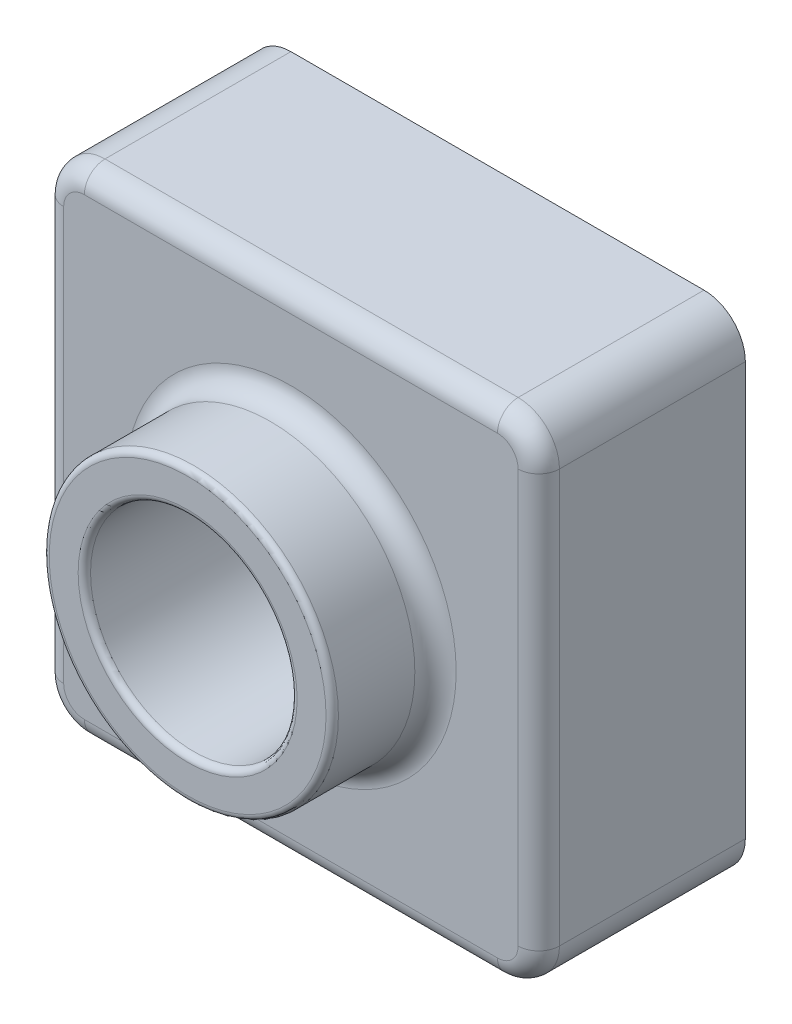
SolidWorks part; units mm, degrees
material "Chrome Stainless Steel"
ref_plane "Front Plane" through (0, 0, 0) normal (0, 0, 1) x (1, 0, 0)
ref_plane "Top Plane" through (0, 0, 0) normal (0, 1, 0) x (1, 0, 0)
ref_plane "Right Plane" through (0, 0, 0) normal (1, 0, 0) x (0, 0, -1)
sketch "Sketch1" plane through (0, 0, 0) normal (0, 0, 1) x (1, 0, 0)
  line L5 (60, -60) -> (-60, -60)
  line L6 (60, -60) -> (60, 60)
  line L7 (60, 60) -> (-60, 60)
  line L8 (-60, -60) -> (-60, 60)
  line L9 (60, -60) -> (-60, 60) construction
  line L10 (60, 60) -> (-60, -60) construction
  point P0 (0, 0)
  dimension "D1" = 120
  dimension "D2" = 120
extrude "Boss-Extrude1" add sketch "Sketch1" along normal blind 50
sketch "Sketch2" plane through (0, 0, 50) normal (0, 0, 1) x (1, 0, 0)
  circle A0 centre (0, 0) radius 35
  dimension "D1" = 70
extrude "Boss-Extrude2" add sketch "Sketch2" along normal blind 25
sketch "Sketch3" plane through (0, 0, 75) normal (0, 0, 1) x (1, 0, 0)
  circle A0 centre (0, 0) radius 25
  circle A1 centre (0, 0) radius 35 construction
  dimension "D1" = 10
extrude "Cut-Extrude1" cut sketch "Sketch3" against normal through all
fillet "Fillet1" radius 10 4 edges at (-60, -60, 25) (-60, 60, 25) (60, 60, 25) (60, -60, 25)
fillet "Fillet2" radius 1.5 2 edges at (35, 0, 75) (25, 0, 75)
fillet "Fillet3" radius 5 9 edges at (-57.0711, 57.0711, 50) (0, 60, 50) (57.0711, 57.0711, 50) (60, 0, 50) (57.0711, -57.0711, 50) (0, -60, 50) (-57.0711, -57.0711, 50) (-60, 0, 50) (35, 0, 50)
shell "Shell1" thickness 2
